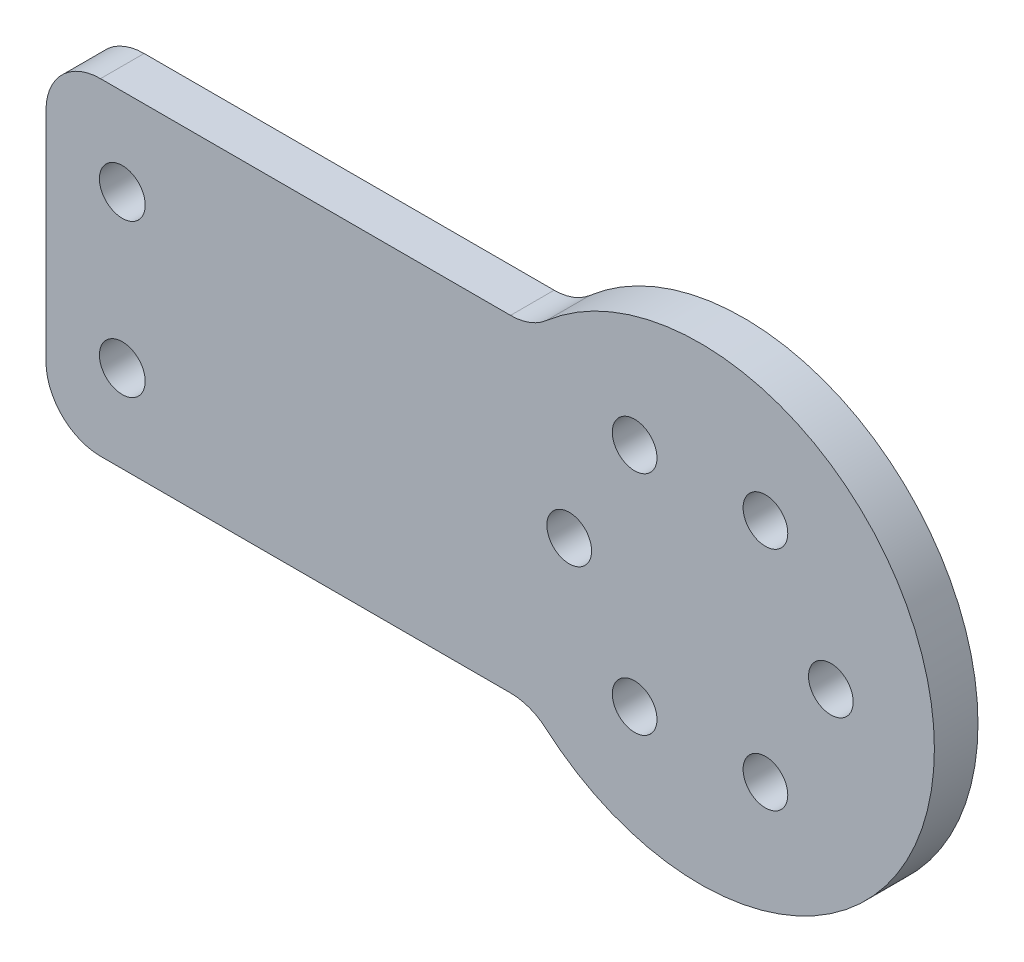
SolidWorks part; units mm, degrees
material "Thornel Mat VMA"
ref_plane "前视基准面" through (0, 0, 0) normal (0, 0, 1) x (1, 0, 0)
ref_plane "上视基准面" through (0, 0, 0) normal (0, 1, 0) x (1, 0, 0)
ref_plane "右视基准面" through (0, 0, 0) normal (1, 0, 0) x (0, 0, -1)
other "Configuration Table"
sketch "草图1" plane through (0, 0, 0) normal (0, 0, 1) x (1, 0, 0)
  line L0 (0, 0) -> (21.5, 0) construction
  line L1 (0, 0) -> (12, 0) construction
  line L2 (0, 0) -> (-60, 0) construction
  line L3 (-60, 0) -> (-60, 15)
  line L4 (-60, 15) -> (-15.4029, 15)
  line L5 (-60, 0) -> (-60, -15)
  line L6 (-60, -15) -> (-15.4029, -15)
  circle A0 centre (0, 0) radius 21.5 construction
  circle A1 centre (12, 0) radius 2.05
  circle A2 centre (6, -10.3923) radius 2.05
  circle A3 centre (-6, -10.3923) radius 2.05
  circle A4 centre (-12, 0) radius 2.05
  circle A5 centre (-6, 10.3923) radius 2.05
  circle A6 centre (6, 10.3923) radius 2.05
  arc A7 (-15.4029, 15) -> (-15.4029, -15) centre (0, 0) cw
  dimension "D1" = 43
  dimension "D2" = 4.1
  dimension "D5" = 60
  dimension "D3" = 12
  dimension "D6" = 15
  dimension "D7" = 15
  dimension "D4" = 6
extrude "凸台-拉伸1" add sketch "草图1" along normal blind 4
sketch "草图2" plane through (0, 0, 4) normal (0, 0, 1) x (1, 0, 0)
  line L0 (-60, 15) -> (-60, -15) construction
  circle A0 centre (-53, 7) radius 2.1
  circle A1 centre (-53, -7) radius 2.1
  point P6 (-60, 0)
  dimension "D1" = 4.2
  dimension "D2" = 4.2
  dimension "D3" = 7
  dimension "D4" = 7
  dimension "D5" = 7
  dimension "D6" = 7
extrude "切除-拉伸1" cut sketch "草图2" against normal through all
fillet "圆角1" radius 5 4 edges at (-60, -15, 2) (-60, 15, 2) (-15.4029, -15, 2) (-15.4029, 15, 2)
